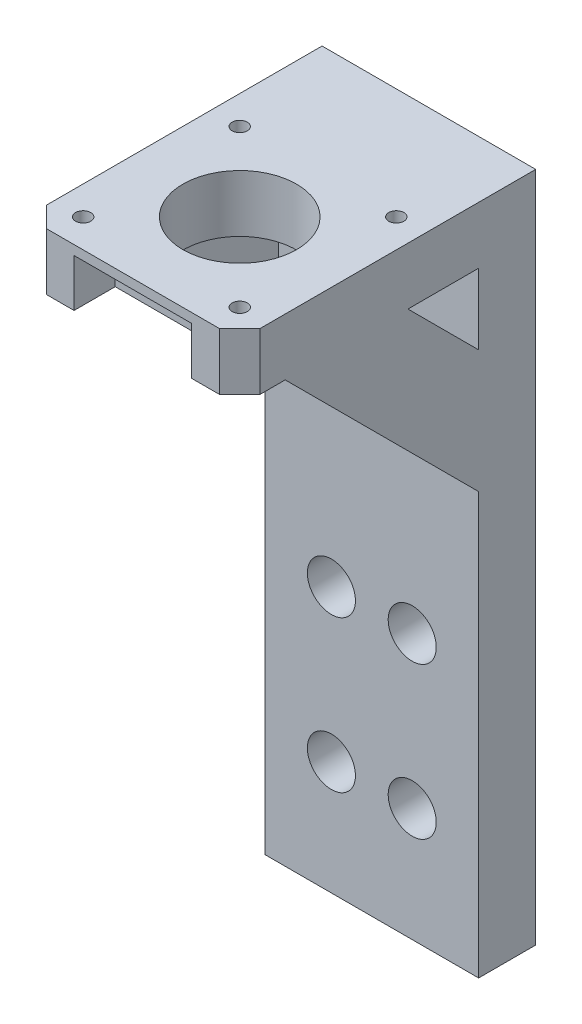
SolidWorks part; units mm, degrees
ref_plane "Front Plane" through (0, 0, 0) normal (0, 0, 1) x (1, 0, 0)
ref_plane "Top Plane" through (0, 0, 0) normal (0, 1, 0) x (1, 0, 0)
ref_plane "Right Plane" through (0, 0, 0) normal (1, 0, 0) x (0, 0, -1)
sketch "Sketch1" plane through (0, 0, 0) normal (0, 1, 0) x (1, 0, 0)
  line L0 (-21.15, 17.15) -> (-17.15, 21.15)
  line L1 (-17.15, -21.15) -> (17.15, -21.15)
  line L2 (-21.15, -17.15) -> (-21.15, 17.15)
  line L3 (-17.15, 21.15) -> (17.15, 21.15)
  line L4 (21.15, -17.15) -> (21.15, 17.15)
  line L5 (-21.15, -21.15) -> (21.15, 21.15) construction
  line L6 (-21.15, 21.15) -> (21.15, -21.15) construction
  line L7 (-17.15, -21.15) -> (-21.15, -17.15)
  line L8 (17.15, -21.15) -> (21.15, -17.15)
  line L9 (17.15, 21.15) -> (21.15, 17.15)
  circle A0 centre (0, 0) radius 11.25
  circle A1 centre (-15.5, 15.5) radius 1.5
  circle A2 centre (15.5, 15.5) radius 1.5
  circle A3 centre (15.5, -15.5) radius 1.5
  circle A4 centre (-15.5, -15.5) radius 1.5
  point P23 (-17.15, 15.5357)
  point P24 (0, 0)
  point P25 (0, 0)
  point P26 (-15.9336, 15.6463)
  point P27 (0, 0)
  dimension "D1" = 22.5
  dimension "D8" = 3
  dimension "D13" = 3
  dimension "D14" = 3
  dimension "D15" = 3
  dimension "D2" = 42.3
  dimension "D3" = 42.3
  dimension "D4" = 31
  dimension "D5" = 31
  dimension "D6" = 31
  dimension "D7" = 31
  dimension "D16" = 15.5
  dimension "D17" = 15.5
extrude "Boss-Extrude1" add sketch "Sketch1" along normal blind 11.3
sketch "Sketch4" plane through (0, 0, -21.15) normal (0, 0, -1) x (-1, 0, 0)
  line L1 (-17.15, 11.3) -> (17.15, 11.3)
  line L2 (-17.15, 11.3) -> (-17.15, 0)
  line L3 (-17.15, 0) -> (17.15, 0)
  line L4 (17.15, 11.3) -> (17.15, 0)
extrude "Boss-Extrude3" add sketch "Sketch4" along normal blind 5
sketch "Sketch5" plane through (0, 11.3, 0) normal (0, 1, 0) x (1, 0, 0)
  line L0 (21.15, 17.15) -> (17.15, 26.15)
  line L1 (17.15, 26.15) -> (17.15, 21.15)
  line L2 (17.15, 21.15) -> (21.15, 17.15)
  line L3 (-17.15, 26.15) -> (-21.15, 17.15)
  line L4 (-21.15, 17.15) -> (-17.15, 21.15)
  line L5 (-17.15, 21.15) -> (-17.15, 26.15)
extrude "Boss-Extrude4" add sketch "Sketch5" against normal up to surface (11.3 mm away) up to face at (0, 0, -5.23)
sketch "Sketch6" plane through (0, 0, -26.15) normal (0, 0, -1) x (-1, 0, 0)
  line L0 (-17.15, 11.3) -> (17.15, 11.3)
  line L1 (-17.15, 11.3) -> (-17.15, -121.7)
  line L2 (17.15, 11.3) -> (17.15, -121.7)
  line L3 (-17.15, -121.7) -> (17.15, -121.7)
  dimension "D1" = 133
extrude "Boss-Extrude5" add sketch "Sketch6" along normal blind 11.3
ref_plane "Plane3" through (-18.5, 0, 0) normal (-1, 0, 0) x (0, 0, 1)
sketch "Sketch9" plane through (0, 11.3, 0) normal (0, 1, 0) x (1, 0, 0)
  line L0 (21.15, 17.15) -> (21.15, 37.45)
  line L1 (21.15, 37.45) -> (17.15, 37.45)
  line L2 (17.15, 37.45) -> (17.15, 26.15)
  line L3 (17.15, 26.15) -> (21.15, 17.15)
  line L4 (-17.15, 37.45) -> (-17.15, 26.15)
  line L5 (-17.15, 26.15) -> (-21.15, 17.15)
  line L6 (-21.15, 17.15) -> (-21.15, 37.45)
  line L7 (-21.15, 37.45) -> (-17.15, 37.45)
extrude "Boss-Extrude6" add sketch "Sketch9" against normal up to surface (133 mm away) up to face at (0, -121.7, -31.8)
sketch "Sketch10" plane through (0, -121.7, 0) normal (0, -1, 0) x (1, 0, 0)
  line L0 (-17.15, -26.15) -> (-21.15, -17.15)
  line L1 (-21.15, -17.15) -> (-21.15, -26.15)
  line L2 (-21.15, -17.15) -> (-21.15, -37.45) construction
  line L3 (-21.15, -26.15) -> (-17.15, -26.15)
  line L4 (17.15, -26.15) -> (21.15, -17.15)
  line L5 (21.15, -17.15) -> (21.15, -26.15)
  line L6 (21.15, -37.45) -> (21.15, -17.15) construction
  line L7 (21.15, -26.15) -> (17.15, -26.15)
extrude "Cut-Extrude1" cut sketch "Sketch10" against normal up to surface (121.7 mm away) up to face at (0, 0, -1.25)
sketch "Sketch11" plane through (-18.5, 0, 0) normal (-1, 0, 0) x (0, 0, 1)
  line L0 (-26.15, -38.3) -> (12.15, 0)
  line L1 (-26.15, 0) -> (-26.15, -121.7) construction
  line L2 (-26.15, 0) -> (17.15, 0) construction
  line L3 (12.15, 0) -> (-12.15, 0)
  line L4 (-12.15, 0) -> (-26.15, -14)
  line L5 (-26.15, -14) -> (-26.15, -38.3)
  point P8 (-12.9057, 0)
  dimension "D1" = 45
  dimension "D2" = 14
  dimension "D3" = 9
extrude "Boss-Extrude8" add sketch "Sketch11" along normal up to surface (2.65 mm away) up to face at (-21.15, -36.8, -15.4833)
sketch "Sketch12" plane through (21.15, 0, 0) normal (1, 0, 0) x (0, 0, -1)
  line L0 (-12.15, 0) -> (12.15, 0)
  line L1 (12.15, 0) -> (26.15, -14)
  line L2 (26.15, -14) -> (26.15, -38.3)
  line L3 (26.15, -38.3) -> (-12.15, 0)
extrude "Boss-Extrude9" add sketch "Sketch12" against normal blind 2.65
sketch "Sketch13" plane through (0, 0, -37.45) normal (0, 0, -1) x (-1, 0, 0)
  line L0 (21.15, -121.7) -> (21.15, 11.3) construction
  line L1 (-21.15, -121.7) -> (21.15, -121.7) construction
  circle A0 centre (8, -69.2) radius 4.7625
  circle A1 centre (-8, -69.2) radius 4.7625
  circle A2 centre (8, -99.2) radius 4.7625
  circle A3 centre (-8, -99.2) radius 4.7625
  point P8 (-11.9242, -103.9502)
  point P9 (0, 0)
  point P10 (0, 0)
  point P11 (0, 0)
  point P12 (8.0997, -69.2251)
  dimension "D1" = 9.525
  dimension "D2" = 9.525
  dimension "D3" = 9.525
  dimension "D4" = 9.525
  dimension "D5" = 16
  dimension "D6" = 30
  dimension "D7" = 13.15
  dimension "D8" = 22.5
extrude "Cut-Extrude2" cut sketch "Sketch13" against normal through all
sketch "Sketch14" plane through (0, 0, 0) normal (0, -1, 0) x (1, 0, 0)
  line L0 (-17.15, 21.15) -> (17.15, 21.15) construction
  line L1 (-11.65, 21.15) -> (11.65, 21.15)
  line L2 (-11.65, 21.15) -> (-11.65, 13)
  line L3 (-11.65, 13) -> (11.65, 13)
  line L4 (11.65, 21.15) -> (11.65, 13)
  circle A0 centre (0, 0) radius 11.25 construction
  dimension "D3" = 13
  dimension "D1" = 5.5
  dimension "D2" = 5.5
extrude "Cut-Extrude3" cut sketch "Sketch14" against normal blind 9.43
sketch "Sketch15" plane through (-21.15, 0, 0) normal (-1, 0, 0) x (0, 0, 1)
  line L0 (-22.8567, -35.0067) -> (-22.8567, -24.2115)
  line L1 (12.15, 0) -> (-26.15, -38.3) construction
  line L2 (-22.8567, -24.2115) -> (-12.0615, -24.2115)
  line L3 (-12.0615, -24.2115) -> (-22.8567, -35.0067)
  line L4 (-37.45, -121.7) -> (-37.45, 11.3) construction
  dimension "D1" = 10.7952
  dimension "D2" = 14.5933
extrude "Cut-Extrude4" cut sketch "Sketch15" against normal up to surface (2.65 mm away) up to face at (-18.5, -13.075, -13.075)
